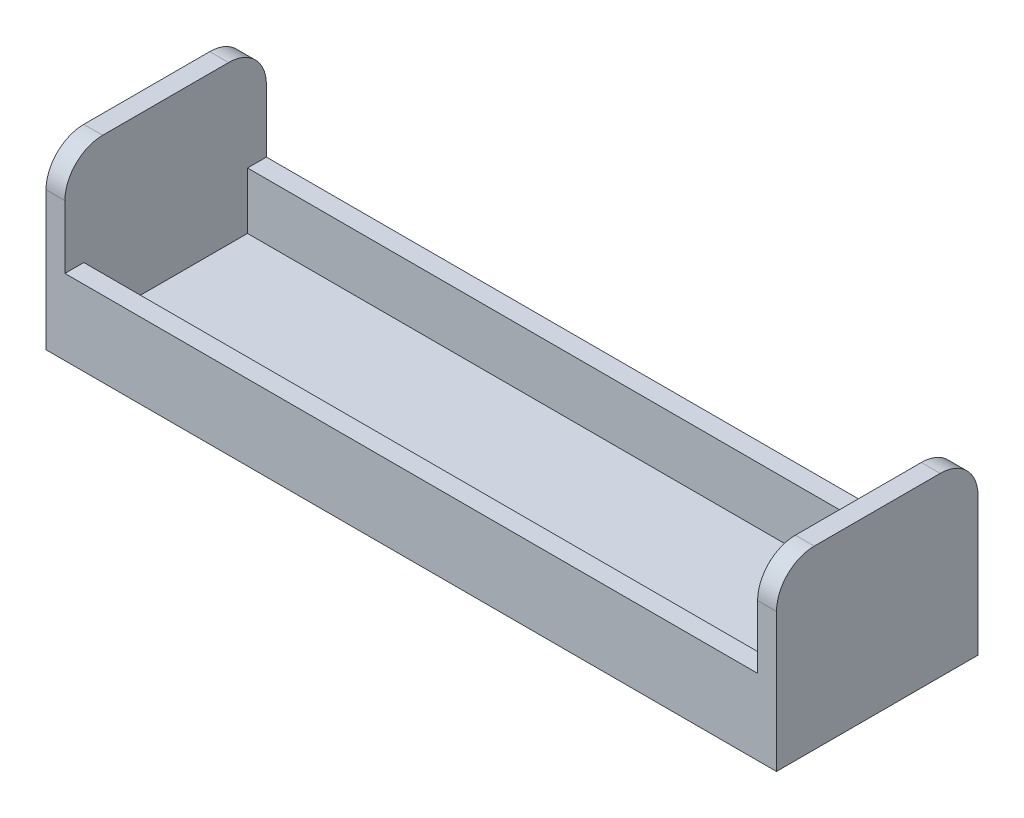
SolidWorks part; units mm, degrees
ref_plane "Front Plane" through (0, 0, 0) normal (0, 0, 1) x (1, 0, 0)
ref_plane "Top Plane" through (0, 0, 0) normal (0, 1, 0) x (1, 0, 0)
ref_plane "Right Plane" through (0, 0, 0) normal (1, 0, 0) x (0, 0, -1)
sketch "Sketch3" plane through (0, 0, 0) normal (1, 0, 0) x (0, 0, -1)
  line L0 (-8, 0) -> (8, 0)
  line L1 (-8, 0) -> (-8, 11)
  line L2 (0, 0) -> (0, 14) construction
  line L3 (8, 0) -> (8, 11)
  line L4 (-5, 14) -> (5, 14)
  arc A0 (-8, 11) -> (-5, 14) centre (-5, 11) cw
  arc A1 (5, 14) -> (8, 11) centre (5, 11) cw
  dimension "D3" = 3
  dimension "D1" = 16
  dimension "D2" = 14
extrude "Boss-Extrude1" add sketch "Sketch3" along normal mid plane 58
sketch "Sketch4" plane through (0, 0, 0) normal (0, 0, 1) x (1, 0, 0)
  line L0 (29, 14) -> (-29, 14) construction
  line L1 (27.5, 6) -> (-27.5, 6)
  line L2 (27.5, 6) -> (27.5, 22)
  line L3 (27.5, 22) -> (-27.5, 22)
  line L4 (-27.5, 6) -> (-27.5, 22)
  line L5 (27.5, 6) -> (-27.5, 22) construction
  line L6 (27.5, 22) -> (-27.5, 6) construction
  line L7 (-29, 11) -> (-29, 0) construction
  line L9 (29, 0) -> (-29, 0) construction
  point P0 (0, 14)
  dimension "D1" = 1.5
  dimension "D2" = 6
extrude "Cut-Extrude1" cut sketch "Sketch4" against normal through all both and the other way through all
sketch "Sketch5" plane through (0, 6, 0) normal (0, 1, 0) x (1, 0, 0)
  line L0 (27.5, 8) -> (27.5, -8) construction
  line L1 (-27.5, -6.5) -> (27.5, -6.5)
  line L2 (-27.5, -6.5) -> (-27.5, 6.5)
  line L3 (-27.5, 6.5) -> (27.5, 6.5)
  line L4 (27.5, -6.5) -> (27.5, 6.5)
  line L5 (-27.5, -6.5) -> (27.5, 6.5) construction
  line L6 (-27.5, 6.5) -> (27.5, -6.5) construction
  line L7 (-27.5, 8) -> (27.5, 8) construction
  point P0 (0, 0)
  dimension "D1" = 1.5
extrude "Cut-Extrude2" cut sketch "Sketch5" against normal offset from surface (4.5 mm away) 1.5 up to face at (0, 0, 0)
